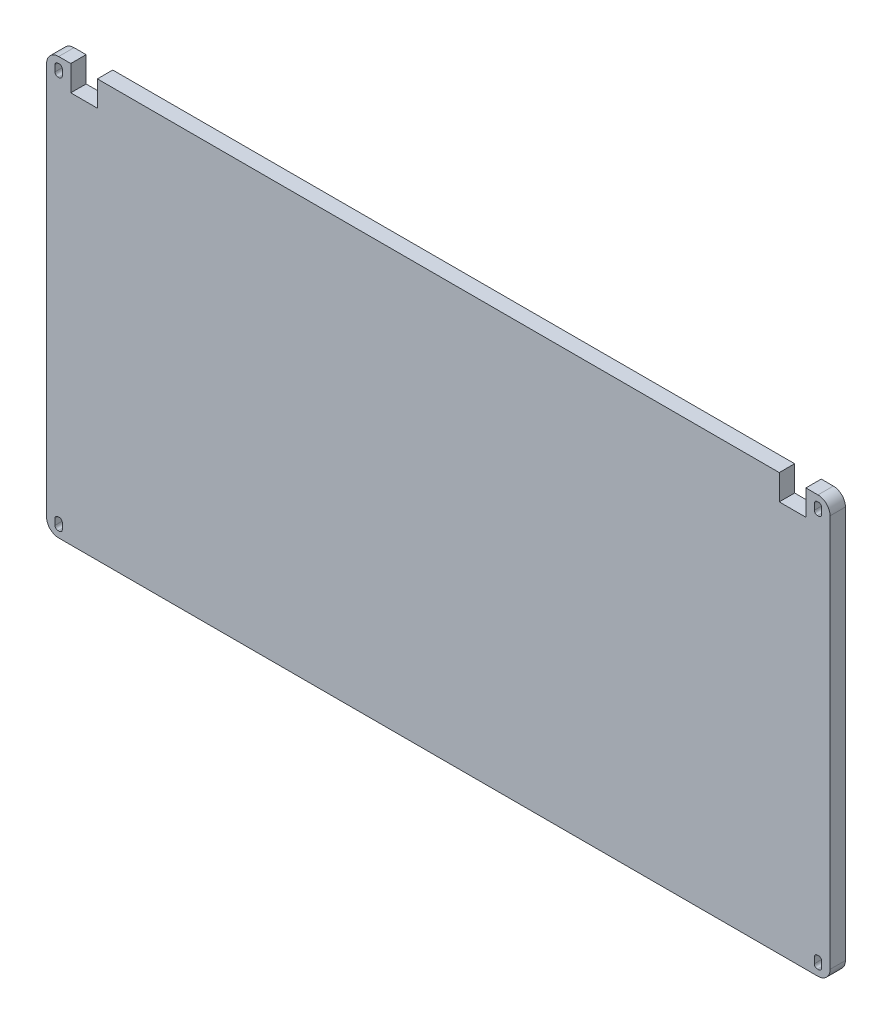
SolidWorks part; units mm, degrees
ref_plane "Front Plane" through (0, 0, 0) normal (0, 0, 1) x (1, 0, 0)
ref_plane "Top Plane" through (0, 0, 0) normal (0, 1, 0) x (1, 0, 0)
ref_plane "Right Plane" through (0, 0, 0) normal (1, 0, 0) x (0, 0, -1)
sketch "Sketch1" plane through (0, 0, 0) normal (0, 0, 1) x (1, 0, 0)
  line L0 (305.7251, 169.7001) -> (325.7251, 169.7001)
  line L1 (-321.9749, 169.7001) -> (-301.9749, 169.7001)
  line L2 (-321.9749, 169.7001) -> (-321.9749, -174.9779)
  line L3 (-321.9749, -174.9779) -> (325.7251, -174.9779)
  line L4 (325.7251, 169.7001) -> (325.7251, -174.9779)
  line L6 (-301.9749, 169.7001) -> (-301.9749, 148.7001)
  line L7 (-301.9749, 148.7001) -> (-279.9749, 148.7001)
  line L8 (-279.9749, 169.7001) -> (-279.9749, 148.7001)
  line L10 (283.7251, 169.7001) -> (283.7251, 148.7001)
  line L11 (283.7251, 148.7001) -> (305.7251, 148.7001)
  line L12 (305.7251, 169.7001) -> (305.7251, 148.7001)
  line L13 (316.2251, -169.9779) -> (315.2251, -169.9779)
  line L14 (318.7251, -167.4779) -> (318.7251, -162.4779)
  line L15 (316.2251, -159.9779) -> (315.2251, -159.9779)
  line L16 (312.7251, -167.4779) -> (312.7251, -162.4779)
  line L17 (-311.4749, -169.9779) -> (-312.4749, -169.9779)
  line L18 (-314.9749, -167.4779) -> (-314.9749, -162.4779)
  line L19 (-311.4749, -159.9779) -> (-312.4749, -159.9779)
  line L20 (-308.9749, -167.4779) -> (-308.9749, -162.4779)
  line L21 (-311.4749, 154.7021) -> (-312.4749, 154.7021)
  line L22 (-314.9749, 157.2021) -> (-314.9749, 162.2021)
  line L23 (-311.4749, 164.7021) -> (-312.4749, 164.7021)
  line L24 (-308.9749, 157.2021) -> (-308.9749, 162.2021)
  line L25 (316.2251, 154.7021) -> (315.2251, 154.7021)
  line L26 (312.7251, 157.2021) -> (312.7251, 162.2021)
  line L27 (316.2251, 164.7021) -> (315.2251, 164.7021)
  line L28 (318.7251, 157.2021) -> (318.7251, 162.2021)
  line L29 (-279.9749, 169.7001) -> (283.7251, 169.7001)
  arc A0 (316.2251, -169.9779) -> (318.7251, -167.4779) centre (316.2251, -167.4779) ccw
  arc A1 (318.7251, -162.4779) -> (316.2251, -159.9779) centre (316.2251, -162.4779) ccw
  arc A2 (315.2251, -169.9779) -> (312.7251, -167.4779) centre (315.2251, -167.4779) cw
  arc A3 (315.2251, -159.9779) -> (312.7251, -162.4779) centre (315.2251, -162.4779) ccw
  arc A4 (-312.4749, -169.9779) -> (-314.9749, -167.4779) centre (-312.4749, -167.4779) cw
  arc A5 (-312.4749, -159.9779) -> (-314.9749, -162.4779) centre (-312.4749, -162.4779) ccw
  arc A6 (-308.9749, -162.4779) -> (-311.4749, -159.9779) centre (-311.4749, -162.4779) ccw
  arc A7 (-311.4749, -169.9779) -> (-308.9749, -167.4779) centre (-311.4749, -167.4779) ccw
  arc A8 (-312.4749, 154.7021) -> (-314.9749, 157.2021) centre (-312.4749, 157.2021) cw
  arc A9 (-312.4749, 164.7021) -> (-314.9749, 162.2021) centre (-312.4749, 162.2021) ccw
  arc A10 (-308.9749, 162.2021) -> (-311.4749, 164.7021) centre (-311.4749, 162.2021) ccw
  arc A11 (-311.4749, 154.7021) -> (-308.9749, 157.2021) centre (-311.4749, 157.2021) ccw
  arc A12 (315.2251, 154.7021) -> (312.7251, 157.2021) centre (315.2251, 157.2021) cw
  arc A13 (315.2251, 164.7021) -> (312.7251, 162.2021) centre (315.2251, 162.2021) ccw
  arc A14 (318.7251, 162.2021) -> (316.2251, 164.7021) centre (316.2251, 162.2021) ccw
  arc A15 (316.2251, 154.7021) -> (318.7251, 157.2021) centre (316.2251, 157.2021) ccw
  point P12 (305.7251, 159.2001)
  point P26 (315.7251, -169.9779)
  point P27 (315.7251, 169.7001)
  dimension "D11" = 2.5
  dimension "D1" = 647.7
  dimension "D2" = 344.678
  dimension "D3" = 21
  dimension "D4" = 22
  dimension "D5" = 21
  dimension "D6" = 22
  dimension "D7" = 20
  dimension "D8" = 20
  dimension "D9" = 169.7001
  dimension "D10" = 321.9749
  dimension "D12" = 6
  dimension "D13" = 10
  dimension "5" = 5
  dimension "78" = 7
  dimension "D16" = 7
  dimension "D17" = 4.998
  dimension "D18" = 7
  dimension "D14" = 2
  dimension "D15" = 2
extrude "Boss-Extrude1" add sketch "Sketch1" along normal blind 12.7 contours L4 L3 L2 L1 L6 L7 L8 L29 L10 L11 L12 L0 | L14 A1 L15 A3 L16 A2 L13 A0 | L20 A6 L19 A5 L18 A4 L17 A7 | L24 A10 L23 A9 L22 A8 L21 A11 | L28 A14 L27 A13 L26 A12 L25 A15
fillet "Fillet1" radius 10 4 edges at (-321.9749, -174.9779, 6.35) (-321.9749, 169.7001, 6.35) (325.7251, -174.9779, 6.35) (325.7251, 169.7001, 6.35)
equation "\"D5@Sketch1\"=\"D3@Sketch1\""
equation "\"D6@Sketch1\"=\"D4@Sketch1\""
equation "\"D8@Sketch1\"=\"D7@Sketch1\""
